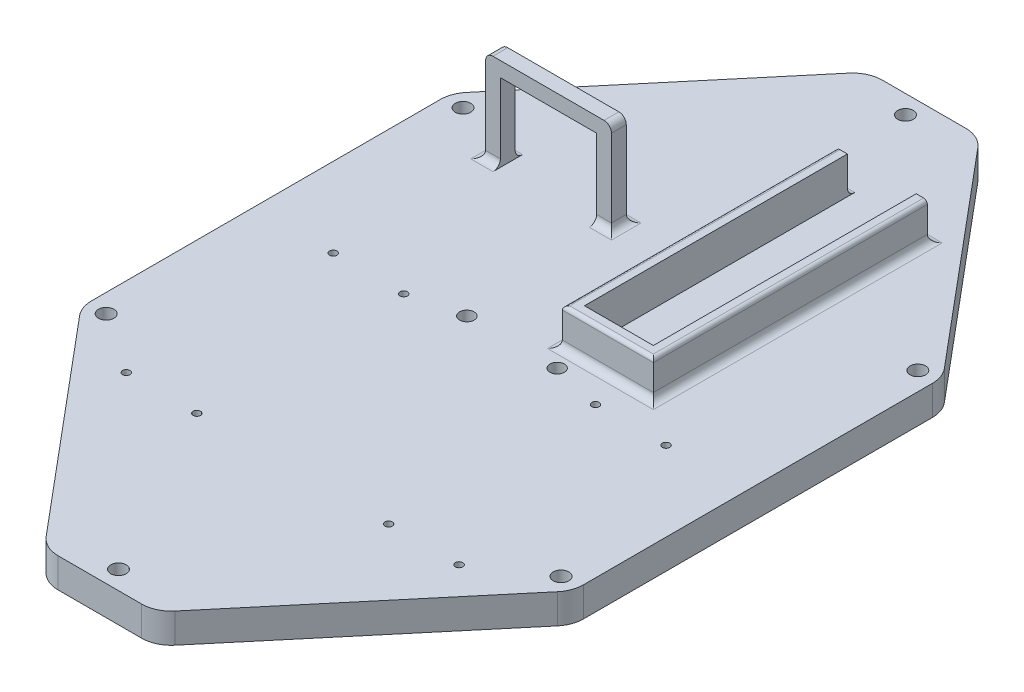
SolidWorks part; units mm, degrees
material "ABS"
ref_plane "Front Plane" through (0, 0, 0) normal (0, 0, 1) x (1, 0, 0)
ref_plane "Top Plane" through (0, 0, 0) normal (0, 1, 0) x (1, 0, 0)
ref_plane "Right Plane" through (0, 0, 0) normal (1, 0, 0) x (0, 0, -1)
sketch "Sketch3" plane through (0, 0, 0) normal (0, 1, 0) x (1, 0, 0)
  line L0 (-66.423, -50) -> (-66.423, 50)
  line L1 (-66.423, 50) -> (-15, 111.2836)
  line L2 (-15, 111.2836) -> (15, 111.2836)
  line L3 (15, 111.2836) -> (66.423, 50)
  line L4 (66.423, 50) -> (66.423, -50)
  line L5 (66.423, -50) -> (15, -111.2836)
  line L6 (15, -111.2836) -> (-15, -111.2836)
  line L7 (-15, -111.2836) -> (-66.423, -50)
  dimension "D1" = 80
  dimension "D2" = 30
  dimension "D3" = 80
  dimension "D4" = 80
  dimension "D5" = 30
  dimension "D6" = 140
  dimension "D7" = 140
  dimension "D8" = 140
  dimension "D9" = 140
extrude "Boss-Extrude2" add sketch "Sketch3" along normal blind 8
sketch "Sketch5" plane through (0, 8, 0) normal (0, 1, 0) x (1, 0, 0)
  line L0 (-66.423, 50) -> (-66.423, -50) construction
  line L1 (-66.423, -50) -> (-15, -111.2836) construction
  line L2 (-15, -111.2836) -> (15, -111.2836) construction
  line L3 (0, -111.2836) -> (0, -88.8775) construction
  line L4 (-66.423, 0) -> (22.8654, 0) construction
  circle A0 centre (0, -106.2836) radius 2.1
  circle A1 centre (-61.423, -48.1801) radius 2.1
  circle A2 centre (0, 106.2836) radius 2.1
  circle A3 centre (-61.423, 48.1801) radius 2.1
  circle A5 centre (61.423, 48.1801) radius 2.1
  circle A7 centre (61.423, -48.1801) radius 2.1
  dimension "D1" = 4.2
  dimension "D2" = 4.2
  dimension "D3" = 5
  dimension "D4" = 5
  dimension "D5" = 5
extrude "Cut-Extrude1" cut sketch "Sketch5" against normal through all
fillet "Fillet1" radius 8 8 edges at (-66.423, 4, -50) (-15, 4, -111.2836) (15, 4, -111.2836) (66.423, 4, -50) (66.423, 4, 50) (-66.423, 4, 50) (15, 4, 111.2836) (-15, 4, 111.2836)
sketch "Sketch6" plane through (0, 8, 0) normal (0, 1, 0) x (1, 0, 0)
  line L0 (-66.423, 47.0882) -> (-66.423, -47.0882) construction
  line L5 (-48.123, -62.3986) -> (-22.723, -62.3986) construction
  line L6 (-48.123, -62.3986) -> (-48.123, -0.1686) construction
  line L11 (-48.123, -0.1686) -> (-22.723, -0.1686) construction
  line L12 (-22.723, -62.3986) -> (-22.723, -0.1686) construction
  line L25 (-48.123, -62.3986) -> (-22.723, -0.1686) construction
  line L26 (-48.123, -0.1686) -> (-22.723, -62.3986) construction
  line L27 (-11.2695, -111.2836) -> (11.2695, -111.2836) construction
  line L28 (-35.423, -0.1686) -> (-35.423, -12.6238) construction
  line L29 (0, -111.2836) -> (0, -36.7752) construction
  circle A0 centre (-44.948, -3.3436) radius 1
  circle A3 centre (-44.948, -59.2236) radius 1
  circle A4 centre (-25.898, -59.2236) radius 1
  circle A5 centre (-25.898, -3.3436) radius 1
  circle A6 centre (44.948, -59.2236) radius 1
  circle A7 centre (25.898, -59.2236) radius 1
  circle A8 centre (44.948, -3.3436) radius 1
  circle A9 centre (25.898, -3.3436) radius 1
  point P0 (-35.423, -31.2836)
  dimension "D5" = 2
  dimension "D8" = 2
  dimension "D1" = 62.23
  dimension "D2" = 25.4
  dimension "D3" = 31
  dimension "D4" = 80
  dimension "D9" = 3.175
  dimension "D10" = 3.175
  dimension "D11" = 55.88
  dimension "D12" = 3.175
extrude "Cut-Extrude2" cut sketch "Sketch6" against normal blind 7
sketch "Sketch8" plane through (0, 8, 0) normal (0, 1, 0) x (1, 0, 0)
  line L0 (8.2953, 79.2836) -> (11.2953, 79.2836)
  line L1 (11.2953, 79.2836) -> (11.2953, 8.2836)
  line L2 (11.2953, 8.2836) -> (29.8953, 8.2836)
  line L3 (29.8953, 8.2836) -> (29.8953, 79.2836)
  line L4 (29.8953, 79.2836) -> (32.8953, 79.2836)
  line L5 (32.8953, 79.2836) -> (32.8953, 5.2836)
  line L6 (32.8953, 5.2836) -> (8.2953, 5.2836)
  line L7 (8.2953, 5.2836) -> (8.2953, 79.2836)
  line L8 (11.2695, 111.2836) -> (-11.2695, 111.2836) construction
  point P2 (20.5953, 8.2836)
  point P9 (20.5953, 5.2836)
  dimension "D1" = 18.6
  dimension "D2" = 74
  dimension "D3" = 3
  dimension "D4" = 74
  dimension "D5" = 3
  dimension "D6" = 3
  dimension "D7" = 106
extrude "Boss-Extrude3" add sketch "Sketch8" along normal blind 10
fillet "Fillet2" radius 2 5 edges at (31.3953, 8, -79.2836) (9.7953, 8, -79.2836) (8.2953, 8, -42.2836) (32.8953, 8, -42.2836) (20.5953, 8, -5.2836)
sketch "Sketch9" plane through (0, 8, 0) normal (0, 1, 0) x (1, 0, 0)
  line L0 (-46.423, 39.2836) -> (-42.423, 39.2836)
  line L1 (-46.423, 39.2836) -> (-46.423, 43.2836)
  line L2 (-46.423, 43.2836) -> (-42.423, 43.2836)
  line L3 (-42.423, 39.2836) -> (-42.423, 43.2836)
  line L4 (-46.423, 39.2836) -> (-42.423, 43.2836) construction
  line L5 (-46.423, 43.2836) -> (-42.423, 39.2836) construction
  line L6 (-16.423, 39.2836) -> (-12.423, 39.2836)
  line L7 (-16.423, 39.2836) -> (-16.423, 43.2836)
  line L8 (-16.423, 43.2836) -> (-12.423, 43.2836)
  line L9 (-12.423, 39.2836) -> (-12.423, 43.2836)
  line L10 (-16.423, 39.2836) -> (-12.423, 43.2836) construction
  line L11 (-16.423, 43.2836) -> (-12.423, 39.2836) construction
  line L12 (-66.423, 47.0882) -> (-66.423, -47.0882) construction
  line L13 (11.2695, 111.2836) -> (-11.2695, 111.2836) construction
  point P0 (-44.423, 41.2836)
  point P5 (-14.423, 41.2836)
  dimension "D1" = 4
  dimension "D2" = 30
  dimension "D3" = 22
  dimension "D4" = 70
extrude "Boss-Extrude4" add sketch "Sketch9" along normal blind 21
sketch "Sketch10" plane through (0, 29, 0) normal (0, 1, 0) x (1, 0, 0)
  line L1 (-46.423, 39.2836) -> (-12.423, 39.2836)
  line L2 (-46.423, 39.2836) -> (-46.423, 43.2836)
  line L3 (-46.423, 43.2836) -> (-12.423, 43.2836)
  line L4 (-12.423, 39.2836) -> (-12.423, 43.2836)
extrude "Boss-Extrude5" add sketch "Sketch10" along normal blind 4
fillet "Fillet3" radius 2 8 edges at (-12.423, 8, -41.2836) (-14.423, 8, -39.2836) (-14.423, 8, -43.2836) (-44.423, 8, -43.2836) (-46.423, 8, -41.2836) (-44.423, 8, -39.2836) (-46.423, 33, -41.2836) (-12.423, 33, -41.2836)
fillet "Fillet4" radius 1 3 edges at (32.8953, 18, -42.2836) (8.2953, 18, -42.2836) (20.5953, 18, -5.2836)
sketch "Sketch11" plane through (0, 8, 0) normal (0, 1, 0) x (1, 0, 0)
  line L0 (66.423, 0) -> (-66.423, 0) construction
  line L1 (66.423, -47.0882) -> (66.423, 47.0882) construction
  line L2 (-66.423, 47.0882) -> (-66.423, -47.0882) construction
  line L3 (0, 0) -> (0, 25.6339) construction
  circle A0 centre (12.2, 0) radius 1.95
  circle A1 centre (-12.2, 0) radius 1.95
  dimension "D1" = 3.9
  dimension "D2" = 3.9
  dimension "D3" = 24.4
  dimension "D4" = 12.2
extrude "Cut-Extrude3" cut sketch "Sketch11" against normal through all
